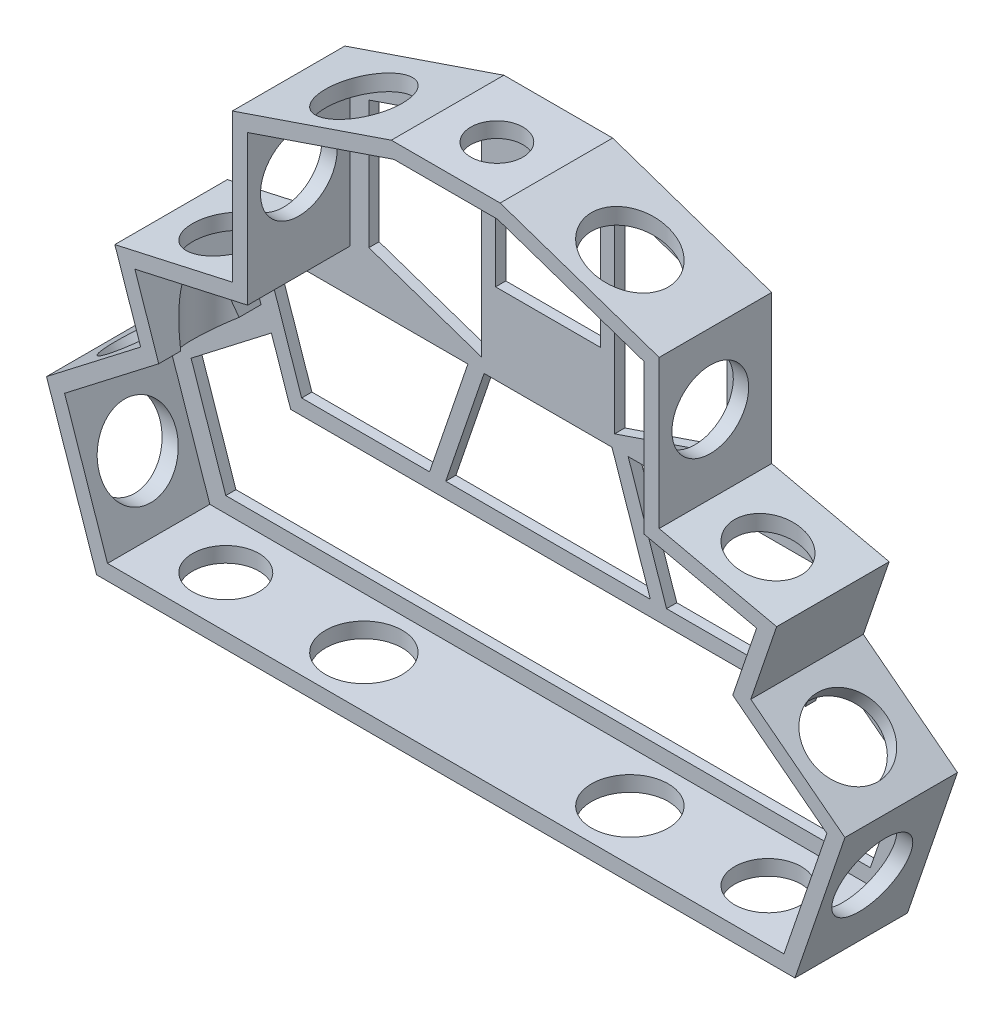
SolidWorks part; units mm, degrees
ref_plane "Front Plane" through (0, 0, 0) normal (0, 0, 1) x (1, 0, 0)
ref_plane "Top Plane" through (0, 0, 0) normal (0, 1, 0) x (1, 0, 0)
ref_plane "Right Plane" through (0, 0, 0) normal (1, 0, 0) x (0, 0, -1)
sketch "Sketch1" plane through (0, 0, 0) normal (0, 0, 1) x (1, 0, 0)
  line L0 (0, 45.5072) -> (0, -87.6181) construction
  line L1 (-48.8406, 0) -> (45.7971, 0) construction
  line L18 (-12.5, -26.0225) -> (12.5, -26.0225)
  line L19 (12.5, -26.0225) -> (20, -48.0225)
  line L20 (-20, -48.0225) -> (20, -48.0225)
  line L21 (-12.5, -26.0225) -> (-20, -48.0225)
  line L40 (15.6695, -26.0225) -> (23.1695, -48.0225)
  line L45 (15.6695, -26.0225) -> (55.6695, -26.0225)
  line L47 (55.6695, -26.0225) -> (48.1695, -48.0225)
  line L49 (48.1695, -48.0225) -> (23.1695, -48.0225)
  line L51 (59.8618, -23.0225) -> (50.3163, -51.0225)
  line L53 (-35.6695, -48.0225) -> (-35.6695, -55.9008) construction
  line L54 (15.6695, -23.0225) -> (59.8618, -23.0225) construction
  line L55 (-15.6695, -26.0225) -> (-55.6695, -26.0225)
  line L56 (14.6468, -23.0225) -> (24.1923, -51.0225) construction
  line L57 (-24.1923, -51.0225) -> (24.1923, -51.0225) construction
  line L58 (50.3163, -51.0225) -> (23.1695, -51.0225) construction
  line L59 (-55.6695, -26.0225) -> (-48.1695, -48.0225)
  line L60 (-48.1695, -48.0225) -> (-23.1695, -48.0225)
  line L61 (-15.6695, -26.0225) -> (-23.1695, -48.0225)
  line L62 (-14.6468, -23.0225) -> (-24.1923, -51.0225) construction
  line L64 (-59.8618, -23.0225) -> (-50.3163, -51.0225)
  line L67 (-11.4773, -23.0225) -> (-21.0227, -51.0225) construction
  line L68 (-11.4773, -23.0225) -> (-59.8618, -23.0225) construction
  line L69 (-14.6468, -23.0225) -> (14.6468, -23.0225) construction
  line L70 (-50.3163, -51.0225) -> (-21.0227, -51.0225) construction
  line L71 (-50.3163, -51.0225) -> (50.3163, -51.0225)
  line L72 (-13.0225, -23.5) -> (-13.0225, 16.5)
  line L73 (-13.0225, 16.5) -> (-35.0225, 9)
  line L74 (-35.0225, 9) -> (-35.0225, -16)
  line L75 (-35.0225, -16) -> (-13.0225, -23.5)
  line L76 (-39.4516, -3.5) -> (45.7971, -3.5) construction
  line L77 (35.0225, 9) -> (35.0225, -16)
  line L78 (13.0225, 16.5) -> (35.0225, 9)
  line L79 (13.0225, -23.5) -> (13.0225, 16.5)
  line L80 (35.0225, -16) -> (13.0225, -23.5)
  line L83 (-10.0225, 20.6923) -> (-38.0225, 11.1468)
  line L84 (-38.0225, 11.1468) -> (-38.0225, -18.1468)
  line L85 (-10.0225, -27.6923) -> (-10.0225, 20.6923) construction
  line L86 (-38.0225, -18.1468) -> (-10.0225, -27.6923) construction
  line L87 (-59.8618, -23.0225) -> (-38.0225, -18.1468)
  line L88 (-10.0225, 20.6923) -> (0, 20.6923)
  line L89 (38.0225, 11.1468) -> (38.0225, -18.1468)
  line L92 (10.0225, 20.6923) -> (38.0225, 11.1468)
  line L93 (10.0225, -27.6923) -> (10.0225, 20.6923) construction
  line L94 (38.0225, -18.1468) -> (10.0225, -27.6923) construction
  line L95 (59.8618, -23.0225) -> (38.0225, -18.1468)
  line L96 (10.0225, 20.6923) -> (0, 20.6923)
  line L97 (-50.3163, -51.0225) -> (-42.3774, -74.31)
  line L98 (-42.3774, -74.31) -> (0, -74.31)
  point P5 (0, 0)
  point P10 (0, 0)
  point P13 (0, 14)
  point P14 (0, 35)
  point P16 (22.4772, 38)
  point P18 (-22.4772, 38)
  point P19 (0, 35)
  point P20 (-14.7629, 11)
  point P33 (14.7629, 11)
  dimension "D3" = 25
  dimension "D4" = 40
  dimension "D5" = 22
  dimension "D6" = 3
  dimension "D8" = 74.31
  dimension "D9" = 20
  dimension "D10" = 3
  dimension "D11" = 40
  dimension "D7" = 12.5
  dimension "D14" = 40
  dimension "D15" = 25
  dimension "D16" = 3.5
  dimension "D17" = 12.5
  dimension "D18" = 20
  dimension "D19" = 22
  dimension "D12" = 3
  dimension "D20" = 3
  dimension "D21" = 3
sketch "Sketch2" plane through (0, 0, 0) normal (0, 0, 1) x (1, 0, 0)
  line L0 (0, 61.1893) -> (0, -109.1422) construction
  line L1 (-59.8618, -23.0225) -> (-50.3163, -51.0225) construction
  line L2 (-59.8618, -23.0225) -> (-38.0225, -18.1468) construction
  line L3 (-38.0225, 11.1468) -> (-38.0225, -18.1468) construction
  line L4 (-10.0225, 20.6923) -> (-38.0225, 11.1468) construction
  line L5 (-10.0225, 20.6923) -> (0, 20.6923) construction
  line L6 (-59.8618, -23.0225) -> (-55.2852, -36.4473)
  line L7 (-59.8618, -23.0225) -> (-38.0225, -18.1468)
  line L8 (-38.0225, 11.1468) -> (-38.0225, -18.1468)
  line L9 (-10.0225, 20.6923) -> (-38.0225, 11.1468)
  line L10 (-10.0225, 20.6923) -> (10.0225, 20.6923)
  line L11 (-42.3782, -74.3077) -> (42.3782, -74.3077)
  line L12 (-42.3782, -74.3077) -> (-65.6215, -74.3077)
  line L13 (-65.6215, -74.3077) -> (-73.6883, -50.645)
  line L14 (-73.6883, -50.645) -> (-55.2852, -36.4473)
  line L15 (73.6883, -50.645) -> (55.2852, -36.4473)
  line L16 (65.6215, -74.3077) -> (73.6883, -50.645)
  line L17 (42.3782, -74.3077) -> (65.6215, -74.3077)
  line L18 (10.0225, 20.6923) -> (38.0225, 11.1468)
  line L19 (38.0225, 11.1468) -> (38.0225, -18.1468)
  line L20 (59.8618, -23.0225) -> (38.0225, -18.1468)
  line L21 (59.8618, -23.0225) -> (55.2852, -36.4473)
  line L22 (-60.7763, -22.5094) -> (-56.1093, -36.1991)
  line L23 (-74.5125, -50.3967) -> (-56.1093, -36.1991)
  line L24 (-66.1224, -75.0077) -> (-74.5125, -50.3967)
  line L25 (-42.3782, -75.0077) -> (-66.1224, -75.0077)
  line L26 (-42.3782, -75.0077) -> (42.3782, -75.0077)
  line L27 (42.3782, -75.0077) -> (66.1224, -75.0077)
  line L28 (66.1224, -75.0077) -> (74.5125, -50.3967)
  line L29 (74.5125, -50.3967) -> (56.1093, -36.1991)
  line L30 (60.7763, -22.5094) -> (56.1093, -36.1991)
  line L31 (60.7763, -22.5094) -> (38.7225, -17.5859)
  line L32 (38.7225, 11.6477) -> (38.7225, -17.5859)
  line L33 (10.1385, 21.3923) -> (38.7225, 11.6477)
  line L34 (-10.1385, 21.3923) -> (10.1385, 21.3923)
  line L35 (-10.1385, 21.3923) -> (-38.7225, 11.6477)
  line L36 (-38.7225, 11.6477) -> (-38.7225, -17.5859)
  line L37 (-60.7763, -22.5094) -> (-38.7225, -17.5859)
  point P18 (0, -74.3077)
  dimension "D1" = 95
  dimension "D2" = 22
  dimension "D3" = 25
  dimension "D4" = 40
  dimension "D5" = 0.7
sketch "Sketch4" plane through (0, 0, 0) normal (0, 0, 1) x (1, 0, 0)
  line L0 (-42.3782, -75.0077) -> (-66.1224, -75.0077) construction
  line L1 (-66.1224, -75.0077) -> (-74.5125, -50.3967) construction
  line L2 (-74.5125, -50.3967) -> (-56.1093, -36.1991) construction
  line L3 (-60.7763, -22.5094) -> (-56.1093, -36.1991) construction
  line L4 (-60.7763, -22.5094) -> (-38.7225, -17.5859) construction
  line L5 (-38.7225, 11.6477) -> (-38.7225, -17.5859) construction
  line L6 (-10.1385, 21.3923) -> (-38.7225, 11.6477) construction
  line L7 (-10.1385, 21.3923) -> (10.1385, 21.3923) construction
  line L8 (66.1224, -75.0077) -> (-66.1224, -75.0077)
  line L9 (-66.1224, -75.0077) -> (-74.5125, -50.3967)
  line L10 (-74.5125, -50.3967) -> (-56.1093, -36.1991)
  line L11 (-60.7763, -22.5094) -> (-56.1093, -36.1991)
  line L12 (-60.7763, -22.5094) -> (-38.7225, -17.5859)
  line L13 (-38.7225, 11.6477) -> (-38.7225, -17.5859)
  line L14 (-10.1385, 21.3923) -> (-38.7225, 11.6477)
  line L15 (-10.1385, 21.3923) -> (10.1385, 21.3923)
  line L16 (0, 33.223) -> (0, -78.7601) construction
  line L17 (0, 45.5072) -> (0, -87.6181) construction
  line L18 (-42.3782, -75.0077) -> (42.3782, -75.0077) construction
  line L19 (10.1385, 21.3923) -> (38.7225, 11.6477)
  line L20 (38.7225, 11.6477) -> (38.7225, -17.5859)
  line L21 (60.7763, -22.5094) -> (38.7225, -17.5859)
  line L22 (60.7763, -22.5094) -> (56.1093, -36.1991)
  line L23 (74.5125, -50.3967) -> (56.1093, -36.1991)
  line L24 (66.1224, -75.0077) -> (74.5125, -50.3967)
  line L25 (10.4701, 23.3923) -> (40.7225, 13.0789)
  line L26 (40.7225, 13.0789) -> (40.7225, -15.9831)
  line L27 (63.389, -21.0435) -> (40.7225, -15.9831)
  line L28 (63.389, -21.0435) -> (58.4642, -35.4898)
  line L29 (76.8674, -49.6874) -> (58.4642, -35.4898)
  line L30 (67.5536, -77.0077) -> (76.8674, -49.6874)
  line L31 (67.5536, -77.0077) -> (-67.5536, -77.0077)
  line L32 (-67.5536, -77.0077) -> (-76.8674, -49.6874)
  line L33 (-76.8674, -49.6874) -> (-58.4642, -35.4898)
  line L34 (-63.389, -21.0435) -> (-58.4642, -35.4898)
  line L35 (-63.389, -21.0435) -> (-40.7225, -15.9831)
  line L36 (-40.7225, 13.0789) -> (-40.7225, -15.9831)
  line L37 (-10.4701, 23.3923) -> (-40.7225, 13.0789)
  line L38 (-10.4701, 23.3923) -> (10.1385, 23.3923)
  line L39 (10.7839, 23.2853) -> (40.7225, 13.0789) construction
  point P11 (0, -74.8077)
  point P19 (0, 21.3923)
  point P26 (0, -75.0077)
  dimension "D1" = 2
extrude "Extrude-Thin3" add sketch "Sketch4" along normal blind 20 thin contours L16 L15 L14 L13 L12 L11 L10 L9 L8 | L15 L16 L8 L24 L23 L22 L21 L20 L19
sketch "Sketch5" plane through (0, 0, 0) normal (0, 0, 1) x (1, 0, 0)
  line L0 (10.6359, 24.3923) -> (41.7225, 13.7945) construction
  line L1 (41.7225, 13.7945) -> (41.7225, -15.1818) construction
  line L2 (64.6954, -20.3105) -> (41.7225, -15.1818) construction
  line L3 (64.6954, -20.3105) -> (59.6416, -35.1351) construction
  line L4 (78.0448, -49.3328) -> (59.6416, -35.1351) construction
  line L5 (68.2692, -78.0077) -> (78.0448, -49.3328) construction
  line L6 (68.2692, -78.0077) -> (-68.2692, -78.0077) construction
  line L7 (-68.2692, -78.0077) -> (-78.0448, -49.3328) construction
  line L8 (-78.0448, -49.3328) -> (-59.6416, -35.1351) construction
  line L9 (-64.6954, -20.3105) -> (-59.6416, -35.1351) construction
  line L10 (-64.6954, -20.3105) -> (-41.7225, -15.1818) construction
  line L11 (-41.7225, 13.7945) -> (-41.7225, -15.1818) construction
  line L12 (-10.6359, 24.3923) -> (10.6359, 24.3923) construction
  line L13 (-10.6359, 24.3923) -> (-41.7225, 13.7945) construction
  line L14 (10.6359, 24.3923) -> (41.7225, 13.7945)
  line L15 (41.7225, 13.7945) -> (41.7225, -15.1818)
  line L16 (64.6954, -20.3105) -> (41.7225, -15.1818)
  line L17 (64.6954, -20.3105) -> (59.6416, -35.1351)
  line L18 (78.0448, -49.3328) -> (59.6416, -35.1351)
  line L19 (68.2692, -78.0077) -> (78.0448, -49.3328)
  line L20 (68.2692, -78.0077) -> (-68.2692, -78.0077)
  line L21 (-68.2692, -78.0077) -> (-78.0448, -49.3328)
  line L22 (-78.0448, -49.3328) -> (-59.6416, -35.1351)
  line L23 (-64.6954, -20.3105) -> (-59.6416, -35.1351)
  line L24 (-64.6954, -20.3105) -> (-41.7225, -15.1818)
  line L25 (-41.7225, 13.7945) -> (-41.7225, -15.1818)
  line L26 (-10.6359, 24.3923) -> (10.6359, 24.3923)
  line L27 (-10.6359, 24.3923) -> (-41.7225, 13.7945)
  line L28 (55.6695, -26.0225) -> (48.1695, -48.0225) construction
  line L29 (-10.25, -10.25) -> (10.25, -10.25)
  line L30 (-10.25, -10.25) -> (-10.25, 10.25)
  line L31 (-10.25, 10.25) -> (10.25, 10.25)
  line L32 (10.25, -10.25) -> (10.25, 10.25)
  line L33 (-10.25, -10.25) -> (10.25, 10.25) construction
  line L34 (-10.25, 10.25) -> (10.25, -10.25) construction
  line L35 (15.6695, -26.0225) -> (23.1695, -48.0225) construction
  line L36 (48.1695, -48.0225) -> (23.1695, -48.0225) construction
  line L37 (15.6695, -26.0225) -> (55.6695, -26.0225) construction
  line L38 (-20, -48.0225) -> (20, -48.0225) construction
  line L39 (12.5, -26.0225) -> (20, -48.0225) construction
  line L40 (-12.5, -26.0225) -> (12.5, -26.0225) construction
  line L41 (-12.5, -26.0225) -> (-20, -48.0225) construction
  line L42 (-15.6695, -26.0225) -> (-23.1695, -48.0225) construction
  line L43 (-48.1695, -48.0225) -> (-23.1695, -48.0225) construction
  line L44 (-55.6695, -26.0225) -> (-48.1695, -48.0225) construction
  line L45 (-15.6695, -26.0225) -> (-55.6695, -26.0225) construction
  line L46 (13.0225, 16.5) -> (35.0225, 9) construction
  line L47 (35.0225, 9) -> (35.0225, -16) construction
  line L48 (13.0225, -23.5) -> (13.0225, 16.5) construction
  line L49 (-35.0225, -16) -> (-13.0225, -23.5) construction
  line L50 (-35.0225, 9) -> (-35.0225, -16) construction
  line L51 (-13.0225, -23.5) -> (-13.0225, 16.5) construction
  line L52 (-13.0225, 16.5) -> (-35.0225, 9) construction
  line L53 (55.6695, -26.0225) -> (48.1695, -48.0225)
  line L54 (15.6695, -26.0225) -> (23.1695, -48.0225)
  line L55 (48.1695, -48.0225) -> (23.1695, -48.0225)
  line L56 (15.6695, -26.0225) -> (55.6695, -26.0225)
  line L57 (-20, -48.0225) -> (20, -48.0225)
  line L58 (12.5, -26.0225) -> (20, -48.0225)
  line L59 (-12.5, -26.0225) -> (12.5, -26.0225)
  line L60 (-12.5, -26.0225) -> (-20, -48.0225)
  line L61 (-15.6695, -26.0225) -> (-23.1695, -48.0225)
  line L62 (-48.1695, -48.0225) -> (-23.1695, -48.0225)
  line L63 (-55.6695, -26.0225) -> (-48.1695, -48.0225)
  line L64 (-15.6695, -26.0225) -> (-55.6695, -26.0225)
  line L65 (13.0225, 16.5) -> (35.0225, 9)
  line L66 (35.0225, 9) -> (35.0225, -16)
  line L67 (13.0225, -23.5) -> (13.0225, 16.5)
  line L68 (-35.0225, -16) -> (-13.0225, -23.5)
  line L69 (-35.0225, 9) -> (-35.0225, -16)
  line L70 (-13.0225, -23.5) -> (-13.0225, 16.5)
  line L71 (-13.0225, 16.5) -> (-35.0225, 9)
  line L72 (35.0225, -16) -> (13.0225, -23.5) construction
  line L73 (35.0225, -16) -> (13.0225, -23.5)
  line L74 (-54.0812, -39.9789) -> (-69.7829, -52.0924)
  line L75 (-69.7829, -52.0924) -> (-63.0084, -71.9643)
  line L76 (-63.0084, -71.9643) -> (63.0084, -71.9643)
  line L77 (0, 45.5072) -> (0, -87.6181) construction
  line L79 (-50.3163, -51.0225) -> (50.3163, -51.0225) construction
  line L80 (50.3163, -51.0225) -> (-50.3163, -51.0225)
  line L81 (-50.3163, -51.0225) -> (-54.0812, -39.9789)
  line L82 (-59.8618, -23.0225) -> (-50.3163, -51.0225) construction
  line L83 (0, 40.4503) -> (0, -81.5416) construction
  line L84 (69.7829, -52.0924) -> (63.0084, -71.9643)
  line L85 (50.3163, -51.0225) -> (54.0812, -39.9789)
  line L86 (54.0812, -39.9789) -> (69.7829, -52.0924)
  point P2 (0, 0)
  point P54 (0, -71.9643)
  point P57 (0, -51.0225)
  dimension "D1" = 20.5
  dimension "D2" = 20.5
extrude "Boss-Extrude2" add sketch "Sketch5" against normal blind 2
sketch "Sketch6" plane through (0, 24.3923, 0) normal (0, 1, 0) x (1, 0, 0)
  line L0 (0, 26.5491) -> (0, -53.6267) construction
  line L1 (-87.4107, -36.2232) -> (98.597, -37.3457) construction
  circle A0 centre (0, -10.0002) radius 5.1
  dimension "D1" = 10.2
  dimension "D2" = 36.75
  dimension "D3" = 26.75
extrude "Cut-Extrude1" cut sketch "Sketch6" against normal blind 5
sketch "Sketch7" plane through (0, 0, 0) normal (0, 1, 0) x (1, 0, 0)
  line L0 (0, 19.5058) -> (0, -50.7281) construction
  line L1 (-86.5898, -10) -> (97.8144, -10) construction
  line L2 (-78.0448, -20) -> (-59.6416, -20) construction
  circle A0 centre (-26, -10) radius 7.5
  circle A1 centre (-53, -10) radius 6.5
  circle A2 centre (26, -10) radius 7.5
  circle A3 centre (53, -10) radius 6.5
  dimension "D2" = 15
  dimension "D3" = 13
  dimension "D4" = 53
  dimension "D1" = 10
  dimension "D5" = 26
extrude "Cut-Extrude2" cut sketch "Sketch7" against normal through all both and the other way through all
sketch "Sketch8" plane through (0, 0, 0) normal (1, 0, 0) x (0, 0, -1)
  line L0 (-10, 45.9959) -> (-10, -102.5538) construction
  circle A0 centre (-10, 0) radius 7.5
  circle A1 centre (-10, -63) radius 7.5
  dimension "D2" = 15
  dimension "D3" = 15
  dimension "D1" = 10
  dimension "D4" = 63
extrude "Cut-Extrude3" cut sketch "Sketch8" against normal through all both and the other way through all
sketch "Sketch9" plane through (5.2605, 6.8187, 0) normal (0.6108, 0.7918, 0) x (0.7918, -0.6108, 0)
  line L0 (-71.3798, -10) -> (140.4284, -10) construction
  circle A0 centre (80, -10) radius 7.5
  dimension "D2" = 15
  dimension "D3" = 80
  dimension "D1" = 10
extrude "Cut-Extrude4" cut sketch "Sketch9" against normal blind 5
sketch "Sketch10" plane through (-5.2605, 6.8187, 0) normal (-0.6108, 0.7918, 0) x (0.7918, 0.6108, 0)
  line L0 (-138.5684, -10) -> (116.485, -10) construction
  circle A0 centre (-80, -10) radius 7.5
  dimension "D2" = 15
  dimension "D3" = 80
  dimension "D1" = 10
extrude "Cut-Extrude5" cut sketch "Sketch10" against normal blind 5
